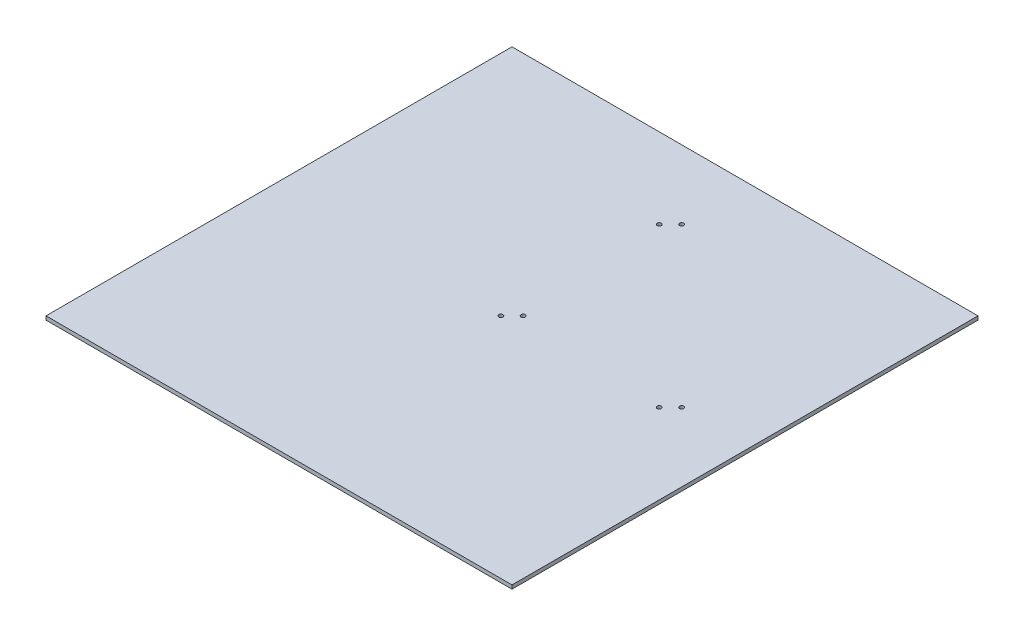
SolidWorks part; units mm, degrees
ref_plane "Plano frontal" through (0, 0, 0) normal (0, 0, 1) x (1, 0, 0)
ref_plane "Plano superior" through (0, 0, 0) normal (0, 1, 0) x (1, 0, 0)
ref_plane "Plano direito" through (0, 0, 0) normal (1, 0, 0) x (0, 0, -1)
sketch "Esboço1" plane through (0, 0, 0) normal (0, 1, 0) x (1, 0, 0)
  line L1 (0, 0) -> (500, 0)
  line L2 (0, 0) -> (0, 500)
  line L3 (0, 500) -> (500, 500)
  line L4 (500, 0) -> (500, 500)
  dimension "D1" = 500
extrude "Ressalto-extrusão1" add sketch "Esboço1" along normal blind 4
sketch "Esboço3" plane through (0, 4, 0) normal (0, 1, 0) x (1, 0, 0)
  line L0 (0, 250) -> (500, 250) construction
  line L1 (0, 500) -> (0, 0) construction
  line L2 (500, 0) -> (500, 500) construction
  line L3 (250, 0) -> (250, 500) construction
  line L4 (0, 0) -> (500, 0) construction
  line L5 (500, 500) -> (0, 500) construction
  line L6 (243.9896, 243.9896) -> (256.0104, 256.0104) construction
  circle A0 centre (256.0104, 256.0104) radius 2.25
  circle A1 centre (243.9896, 243.9896) radius 2.25
  circle A2 centre (426.0104, 256.0104) radius 2.25
  circle A3 centre (413.9896, 243.9896) radius 2.25
  circle A4 centre (243.9896, 413.9896) radius 2.25
  circle A5 centre (256.0104, 426.0104) radius 2.25
  point P14 (250, 250)
  point P15 (250, 250)
  dimension "D3" = 4.5
  dimension "D4" = 4.5
  dimension "D1" = 45
  dimension "D2" = 17
  dimension "D5" = 2
  dimension "D6" = 2
extrude "Corte-extrusão1" cut sketch "Esboço3" against normal up to surface (4 mm away) up to face at (250, 0, -250)
